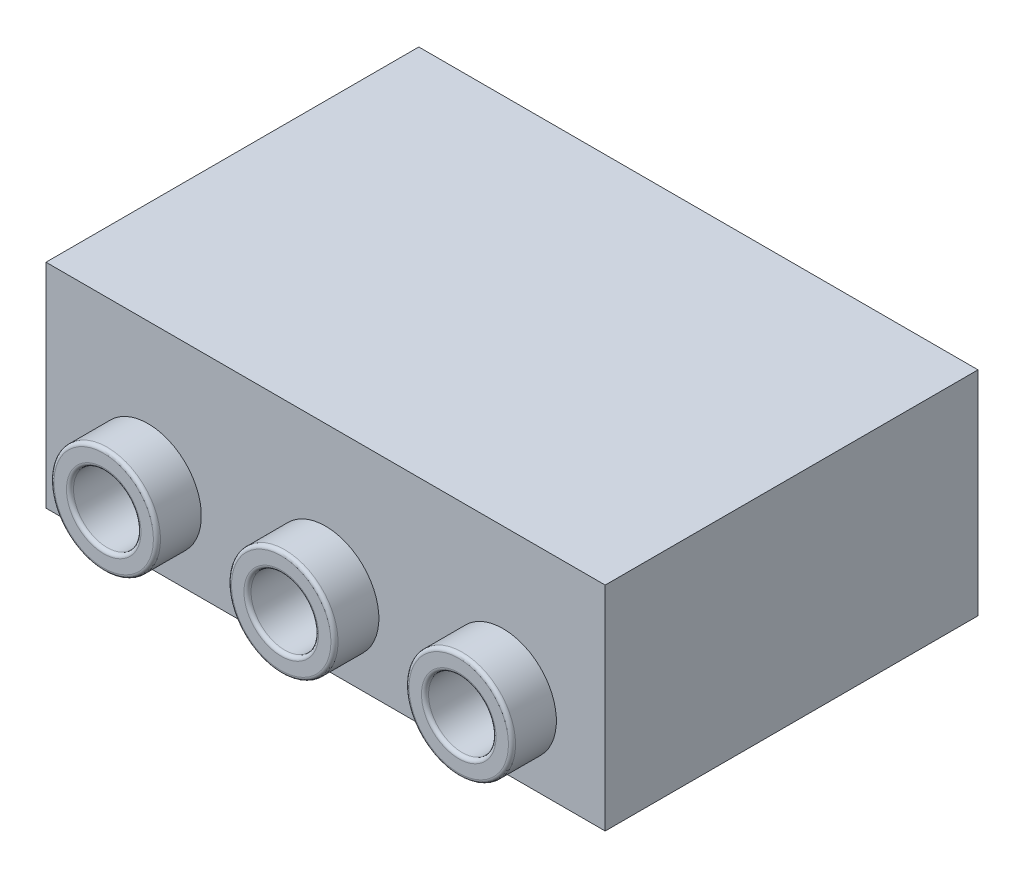
SolidWorks part; units mm, degrees
ref_plane "Front Plane" through (0, 0, 0) normal (0, 0, 1) x (1, 0, 0)
ref_plane "Top Plane" through (0, 0, 0) normal (0, 1, 0) x (1, 0, 0)
ref_plane "Right Plane" through (0, 0, 0) normal (1, 0, 0) x (0, 0, -1)
sketch "Sketch1" plane through (0, 0, 0) normal (0, 1, 0) x (1, 0, 0)
  line L1 (-15.75, -10.5) -> (15.75, -10.5)
  line L2 (-15.75, -10.5) -> (-15.75, 10.5)
  line L3 (-15.75, 10.5) -> (15.75, 10.5)
  line L4 (15.75, -10.5) -> (15.75, 10.5)
  line L5 (-15.75, -10.5) -> (15.75, 10.5) construction
  line L6 (-15.75, 10.5) -> (15.75, -10.5) construction
  point P0 (0, 0)
  dimension "D1" = 31.5
  dimension "D2" = 21
extrude "Boss-Extrude1" add sketch "Sketch1" along normal blind 12
sketch "Sketch2" plane through (0, 0, 10.5) normal (0, 0, 1) x (1, 0, 0)
  line L0 (-15.75, 0) -> (15.75, 0) construction
  circle A0 centre (0, 4) radius 3
  circle A1 centre (10, 4) radius 3
  circle A2 centre (-10, 4) radius 3
  circle A3 centre (-10, 4) radius 1.9
  circle A4 centre (0, 4) radius 1.9
  circle A5 centre (10, 4) radius 1.9
  dimension "D1" = 6
  dimension "D2" = 6
  dimension "D3" = 6
  dimension "D4" = 4
  dimension "D5" = 4
  dimension "D6" = 4
  dimension "D7" = 10
  dimension "D8" = 10
  dimension "D9" = 1.1
extrude "Boss-Extrude2" add sketch "Sketch2" along normal blind 2.5
fillet "Fillet1" radius 0.2 6 edges at (-8.1, 4, 13) (1.9, 4, 13) (11.9, 4, 13) (13, 4, 13) (3, 4, 13) (-7, 4, 13)
sketch "Sketch3" plane through (0, 0, 10.5) normal (0, 0, 1) x (1, 0, 0)
  circle A0 centre (-10, 4) radius 1.9
  circle A1 centre (0, 4) radius 1.9
  circle A2 centre (10, 4) radius 1.9
extrude "Cut-Extrude1" cut sketch "Sketch3" against normal blind 6
